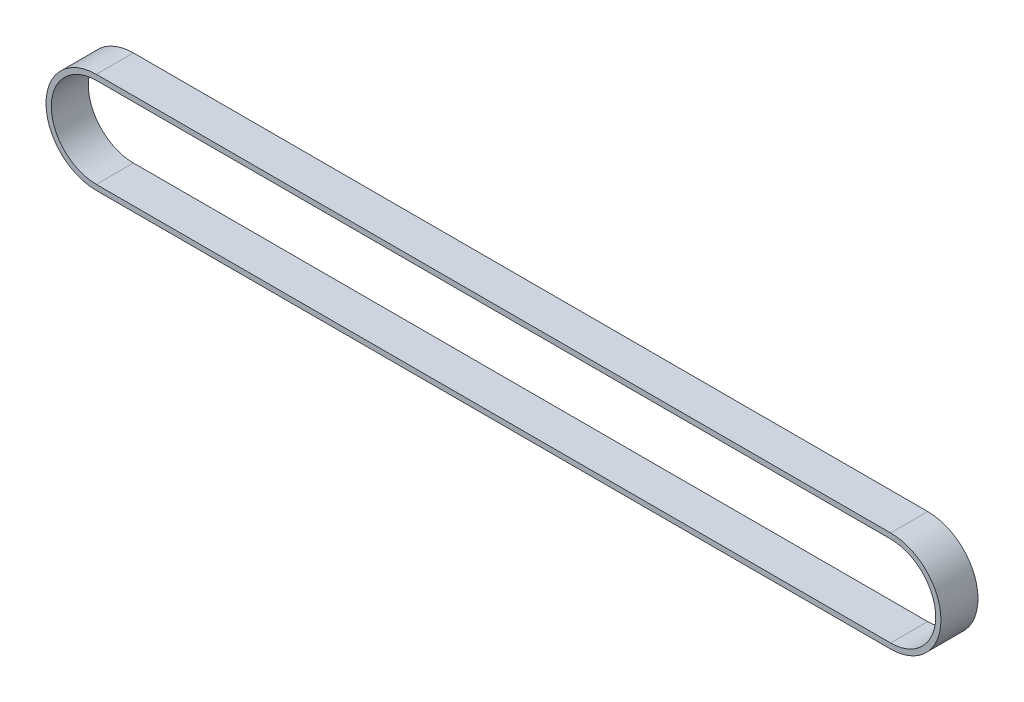
SolidWorks part; units mm, degrees
ref_plane "前视基准面" through (0, 0, 0) normal (0, 0, 1) x (1, 0, 0)
ref_plane "上视基准面" through (0, 0, 0) normal (0, 1, 0) x (1, 0, 0)
ref_plane "右视基准面" through (0, 0, 0) normal (1, 0, 0) x (0, 0, -1)
other "Configuration Table"
sketch "草图1" plane through (0, 0, 0) normal (0, 0, 1) x (1, 0, 0)
  line L0 (-13.9171, 0) -> (286.0829, 0) construction
  line L1 (-13.9171, 17) -> (286.0829, 17)
  line L2 (-13.9171, -17) -> (286.0829, -17)
  arc A0 (-13.9171, 17) -> (-13.9171, -17) centre (-13.9171, 0) ccw
  arc A1 (286.0829, -17) -> (286.0829, 17) centre (286.0829, 0) ccw
  point P3 (136.0829, 0)
  dimension "D1" = 17
  dimension "D2" = 300
extrude "拉伸-薄壁1" add sketch "草图1" along normal blind 14 thin thin type one direction wall 2
